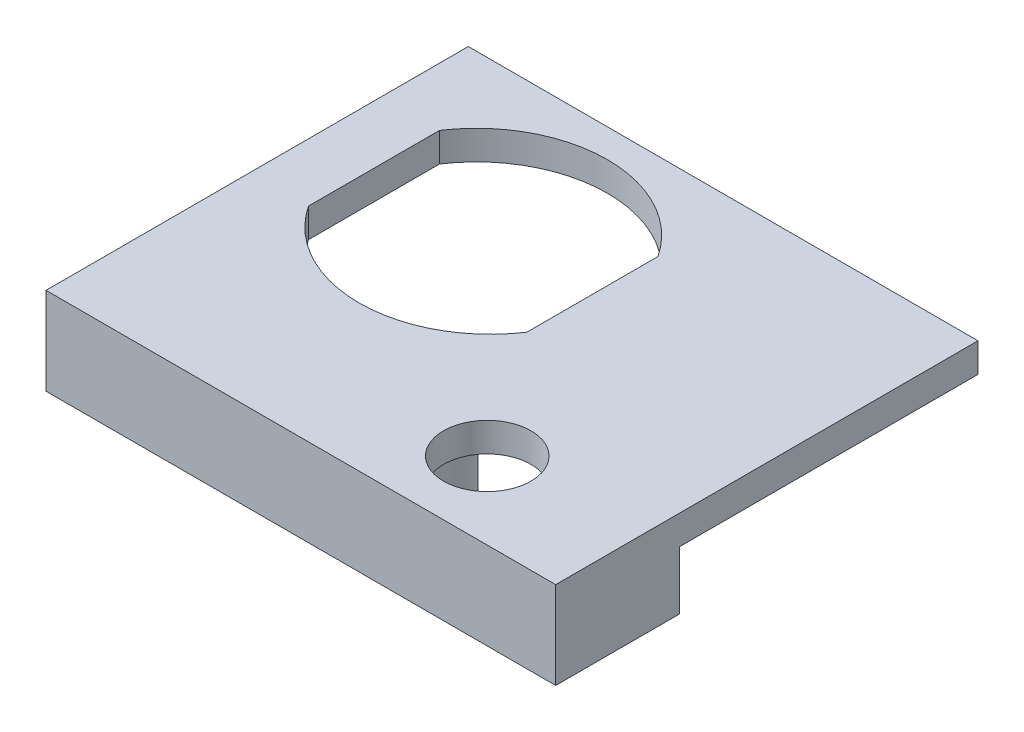
SolidWorks part; units mm, degrees
ref_plane "Alzado" through (0, 0, 0) normal (0, 0, 1) x (1, 0, 0)
ref_plane "Planta" through (0, 0, 0) normal (0, 1, 0) x (1, 0, 0)
ref_plane "Vista lateral" through (0, 0, 0) normal (1, 0, 0) x (0, 0, -1)
sketch "Croquis1" plane through (0, 0, 0) normal (0, 1, 0) x (1, 0, 0)
  line L1 (-8.75, 7.25) -> (-6.75, 7.25)
  line L2 (-8.75, 7.25) -> (-8.75, -7.25)
  line L3 (-8.75, -7.25) -> (8.75, -7.25)
  line L4 (8.75, 7.25) -> (8.75, -7.25)
  line L6 (0.75, 7.25) -> (8.75, 7.25)
  line L7 (-6.75, 7.25) -> (0.75, 7.25)
  line L8 (-6.75, 4.2625) -> (-6.75, -0.2375)
  line L9 (0.75, 4.2625) -> (0.75, -0.2375)
  line L10 (0.75, 7.25) -> (0.75, 4.2625) construction
  circle A0 centre (3.75, -4.6) radius 1.5
  arc A4 (-6.75, -0.2375) -> (0.75, -0.2375) centre (-3, 2.25) ccw
  arc A5 (-6.75, 4.2625) -> (0.75, 4.2625) centre (-3, 1.7751) cw
  point P6 (-8.75, 0)
  point P8 (0, -7.25)
  point P17 (-3, -2.25)
  dimension "D4" = 3
  dimension "D10" = 4.5
  dimension "D11" = 4.5
  dimension "D1" = 17.5
  dimension "D2" = 2.65
  dimension "D3" = 5
  dimension "D5" = 14.5
  dimension "D6" = 4.5
  dimension "D7" = 2
  dimension "D8" = 8
  dimension "D9" = 5
extrude "Saliente-Extruir1" add sketch "Croquis1" along normal blind 1
sketch "Croquis2" plane through (0, 0, 0) normal (0, -1, 0) x (1, 0, 0)
  line L0 (8.75, 7.25) -> (8.75, -7.25) construction
  line L1 (-8.75, 7.25) -> (8.75, 7.25)
  line L2 (-8.75, 7.25) -> (-8.75, 3)
  line L3 (-8.75, 3) -> (1.8291, 3)
  line L4 (8.75, 7.25) -> (8.75, 3)
  line L5 (5.6709, 3) -> (8.75, 3)
  arc A0 (5.6709, 3) -> (1.8291, 3) centre (3.75, 4.6) ccw
  dimension "D1" = 5
  dimension "D2" = 4.25
extrude "Saliente-Extruir2" add sketch "Croquis2" along normal blind 2
sketch "Croquis3" plane through (0, 0, 0) normal (0, -1, 0) x (1, 0, 0)
  line L0 (0.75, 0.2375) -> (0.75, -4.2625) construction
  line L1 (1.75, 2.25) -> (3.75, 2.25)
  line L2 (1.75, 2.25) -> (1.75, -3.75)
  line L3 (1.75, -3.75) -> (3.75, -3.75)
  line L4 (3.75, 2.25) -> (3.75, -3.75)
  arc A0 (0.75, 0.2375) -> (-6.75, 0.2375) centre (-3, -2.25) ccw construction
  point P7 (-3, 2.25)
  dimension "D1" = 6
  dimension "D2" = 0
  dimension "D3" = 1
  dimension "D4" = 2
extrude "Saliente-Extruir3" add sketch "Croquis3" along normal blind 0.5
